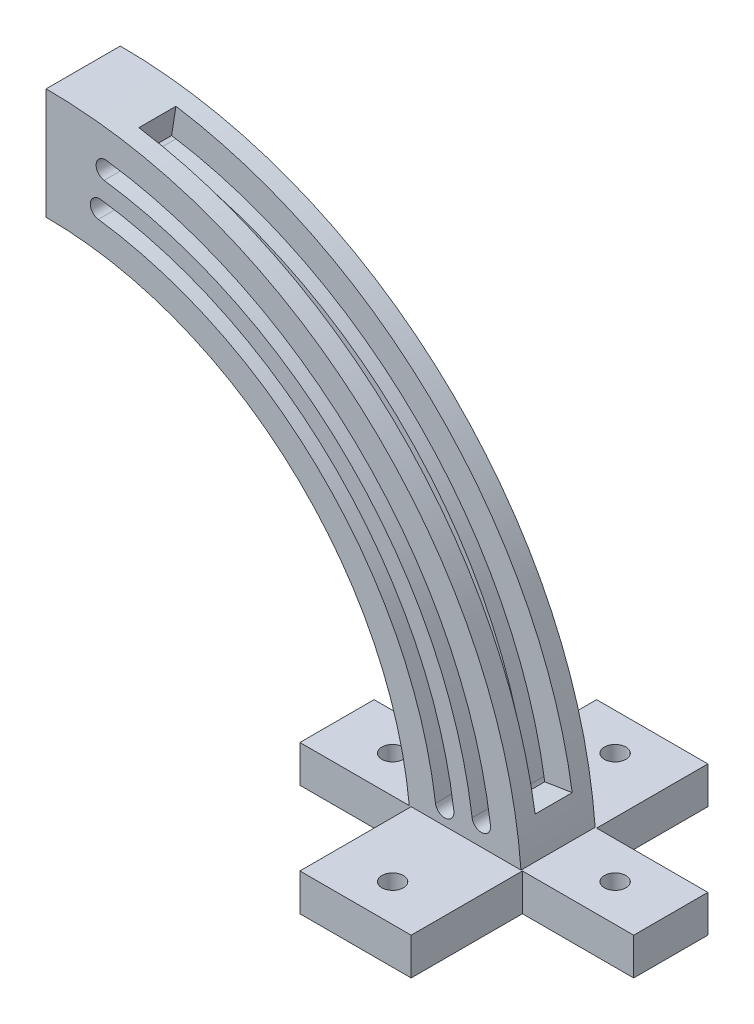
SolidWorks part; units mm, degrees
ref_plane "Front Plane" through (0, 0, 0) normal (0, 0, 1) x (1, 0, 0)
ref_plane "Top Plane" through (0, 0, 0) normal (0, 1, 0) x (1, 0, 0)
ref_plane "Right Plane" through (0, 0, 0) normal (1, 0, 0) x (0, 0, -1)
sketch "Sketch1" plane through (0, 0, 0) normal (0, 0, 1) x (1, 0, 0)
  line L0 (0, 163.1) -> (0, 125)
  line L1 (125, 0) -> (163.1, 0)
  arc A0 (125, 0) -> (0, 125) centre (0, 0) ccw
  arc A1 (163.1, 0) -> (0, 163.1) centre (0, 0) ccw
  dimension "D1" = 125
  dimension "D2" = 38.1
extrude "Boss-Extrude1" add sketch "Sketch1" along normal mid plane 25.4
sketch "Sketch3" plane through (0, 0, 0) normal (0, 0, 1) x (1, 0, 0)
  line L1 (25.4, 161.1101) -> (19.4666, 123.4749)
  line L2 (161.1101, 25.4) -> (123.4749, 19.4666)
  line L3 (125, 0) -> (163.1, 0)
  line L4 (0, 163.1) -> (0, 125)
  arc A2 (125, 0) -> (0, 125) centre (0, 0) ccw
  arc A3 (163.1, 0) -> (0, 163.1) centre (0, 0) ccw
  arc A4 (123.4749, 19.4666) -> (19.4666, 123.4749) centre (0, 0) ccw
  arc A5 (161.1101, 25.4) -> (25.4, 161.1101) centre (0, 0) ccw
  dimension "D2" = 25.4
  dimension "D3" = 25.4
  dimension "D1" = 0
extrude "Cut-Extrude1" cut sketch "Sketch3" against normal mid plane 12.7
sketch "Sketch4" plane through (0, 0, 12.7) normal (0, 0, 1) x (1, 0, 0)
  line L0 (25.4, 161.1101) -> (19.4666, 123.4749) construction
  line L1 (25.4, 161.1101) -> (19.4666, 123.4749) construction
  line L2 (123.4749, 19.4666) -> (161.1101, 25.4) construction
  line L3 (123.4749, 19.4666) -> (161.1101, 25.4) construction
  line L4 (18.3027, 136.4798) -> (20.2805, 149.0249) construction
  line L5 (149.0249, 20.2805) -> (136.4798, 18.3027) construction
  arc A0 (17.8807, 133.333) -> (133.333, 17.8807) centre (0, 0) cw
  arc A1 (18.7247, 139.6267) -> (139.6267, 18.7247) centre (0, 0) cw
  arc A2 (139.6267, 18.7247) -> (133.333, 17.8807) centre (136.4798, 18.3027) cw
  arc A3 (18.7247, 139.6267) -> (17.8807, 133.333) centre (18.3027, 136.4798) ccw
  arc A4 (19.8524, 145.8789) -> (145.8789, 19.8524) centre (0, 0) cw
  arc A5 (20.7086, 152.1709) -> (152.1709, 20.7086) centre (0, 0) cw
  arc A6 (152.1709, 20.7086) -> (145.8789, 19.8524) centre (149.0249, 20.2805) cw
  arc A7 (20.7086, 152.1709) -> (19.8524, 145.8789) centre (20.2805, 149.0249) ccw
  arc A8 (19.2916, 142.7524) -> (22.4333, 142.2925) centre (0, 0) ccw
  point P25 (19.2916, 142.7524)
  dimension "D1" = 3.175
  dimension "D2" = 12.7
extrude "Cut-Extrude2" cut sketch "Sketch4" against normal through all contours A1 A3 A0 A2 | A5 A7 A4 A6
sketch "Sketch5" plane through (0, 0, 0) normal (0, 1, 0) x (1, 0, 0)
  line L0 (163.1, -12.7) -> (201.2, -12.7)
  line L1 (125, 50.8) -> (163.1, 50.8)
  line L2 (125, 50.8) -> (125, 12.7)
  line L3 (125, -50.8) -> (163.1, -50.8)
  line L4 (163.1, 50.8) -> (163.1, 12.7)
  line L5 (125, 50.8) -> (163.1, -50.8) construction
  line L6 (125, -50.8) -> (163.1, 50.8) construction
  line L7 (86.9, 12.7) -> (125, 12.7)
  line L8 (86.9, 12.7) -> (86.9, -12.7)
  line L9 (86.9, -12.7) -> (125, -12.7)
  line L10 (201.2, 12.7) -> (201.2, -12.7)
  line L11 (86.9, 12.7) -> (201.2, -12.7) construction
  line L12 (86.9, -12.7) -> (201.2, 12.7) construction
  line L13 (125, -12.7) -> (125, -50.8)
  line L14 (163.1, 12.7) -> (201.2, 12.7)
  line L15 (163.1, -12.7) -> (163.1, -50.8)
  line L16 (163.1, -12.7) -> (163.1, 12.7) construction
  line L17 (105.95, 0) -> (182.15, 0) construction
  circle A0 centre (105.95, 0) radius 3.675
  circle A1 centre (182.15, 0) radius 3.675
  circle A2 centre (144.05, -38.1) radius 3.675
  circle A3 centre (144.05, 38.1) radius 3.675
  point P0 (144.05, 0)
  point P5 (144.05, 0)
  point P27 (144.05, 0)
  point P29 (86.9, 0)
  dimension "D2" = 7.35
  dimension "D1" = 38.1
  dimension "D3" = 76.2
  dimension "D4" = 76.2
extrude "Boss-Extrude2" add sketch "Sketch5" along normal blind 12.7
equation "\"D4@Sketch5\"=\"D3@Sketch5\""
